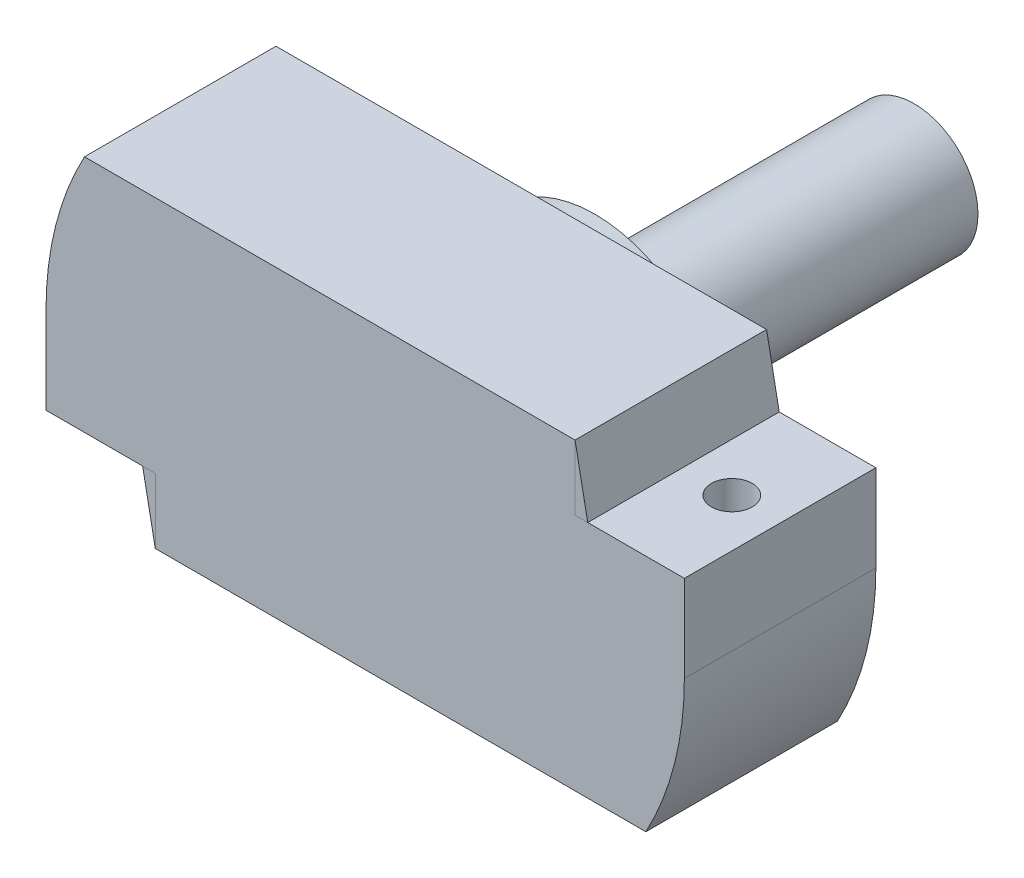
SolidWorks part; units mm, degrees
ref_plane "前视基准面" through (0, 0, 0) normal (0, 0, 1) x (1, 0, 0)
ref_plane "上视基准面" through (0, 0, 0) normal (0, 1, 0) x (1, 0, 0)
ref_plane "右视基准面" through (0, 0, 0) normal (1, 0, 0) x (0, 0, -1)
other "Configuration Table"
sketch "草图1" plane through (0, 0, 0) normal (0, 0, 1) x (1, 0, 0)
  circle A0 centre (0, 0) radius 5
  dimension "D1" = 10
extrude "凸台-拉伸1" add sketch "草图1" along normal blind 25
sketch "草图2" plane through (0, 0, 25) normal (0, 0, 1) x (1, 0, 0)
  circle A2 centre (0, 0) radius 10
  circle A3 centre (0, 0) radius 10
  dimension "D1" = 5
extrude "凸台-拉伸2" add sketch "草图2" along normal blind 3
sketch "草图3" plane through (0, 0, 28) normal (0, 0, 1) x (1, 0, 0)
  line L1 (-25, 11.9) -> (25, 11.9)
  line L2 (-25, 11.9) -> (-25, -11.9)
  line L3 (-25, -11.9) -> (25, -11.9)
  line L4 (25, 11.9) -> (25, -11.9)
  dimension "D1" = 23.8
  dimension "D2" = 50
  dimension "D3" = 25
  dimension "D4" = 11.9
extrude "凸台-拉伸3" add sketch "草图3" along normal blind 15
sketch "草图4" plane through (0, 0, 43) normal (0, 0, 1) x (1, 0, 0)
  line L4 (-25, 11.9) -> (-25, -11.9)
  line L5 (-25, -11.9) -> (25, -11.9)
  line L6 (25, -11.9) -> (25, 11.9)
  line L7 (25, 11.9) -> (-25, 11.9)
  line L8 (-25, 11.9) -> (-25, 0)
  line L9 (21.9861, -11.9) -> (25, -11.9)
  line L10 (25, -11.9) -> (25, 0)
  line L11 (-21.9861, 11.9) -> (-25, 11.9)
  arc A0 (21.9861, -11.9) -> (25, 0) centre (0, 0) ccw
  arc A1 (-21.9861, 11.9) -> (-25, 0) centre (0, 0) ccw
  dimension "D1" = 50
  dimension "D2" = 0
extrude "切除-拉伸1" cut sketch "草图4" against normal through all
sketch "草图5" plane through (0, 11.9, 0) normal (0, 1, 0) x (1, 0, 0)
  line L0 (25, -28) -> (-21.9861, -28) construction
  line L1 (16.44, -28) -> (25, -28)
  line L2 (16.44, -28) -> (16.44, -43)
  line L3 (16.44, -43) -> (25, -43)
  line L4 (25, -28) -> (25, -43)
  dimension "D1" = 8.56
extrude "切除-拉伸2" cut sketch "草图5" against normal blind 5.1
sketch "草图6" plane through (0, 6.8, 0) normal (0, 1, 0) x (1, 0, 0)
  line L0 (16.44, -28) -> (16.44, -43) construction
  circle A0 centre (21.22, -35.5) radius 1.6
  dimension "D1" = 3.2
  dimension "D2" = 4.78
extrude "切除-拉伸3" cut sketch "草图6" against normal blind 10
sketch "草图7" plane through (0, -11.9, 0) normal (0, -1, 0) x (1, 0, 0)
  line L0 (-25, 28) -> (21.9861, 28) construction
  line L1 (-25, 43) -> (-16.44, 43)
  line L2 (-25, 43) -> (-25, 28)
  line L3 (-25, 28) -> (-16.44, 28)
  line L4 (-16.44, 43) -> (-16.44, 28)
  dimension "D1" = 8.56
extrude "切除-拉伸4" cut sketch "草图7" against normal blind 5.1
sketch "草图8" plane through (0, -6.8, 0) normal (0, -1, 0) x (1, 0, 0)
  line L1 (-16.44, 28) -> (-16.44, 43) construction
  circle A0 centre (-21.22, 35.5) radius 1.6
  dimension "D1" = 3.2
  dimension "D2" = 4.78
extrude "切除-拉伸5" cut sketch "草图8" against normal blind 10
sketch "草图9" plane through (0, 0, 43) normal (0, 0, 1) x (1, 0, 0)
  line L0 (16.44, 11.9) -> (17.4313, 6.8)
  line L1 (16.44, 6.8) -> (25, 6.8) construction
  line L2 (-16.44, -11.9) -> (-17.4313, -6.8)
  line L3 (-16.44, -6.8) -> (-25, -6.8) construction
  line L4 (-17.4313, -6.8) -> (-16.44, -6.8)
  line L5 (-16.44, -6.8) -> (-16.44, -11.9)
  line L6 (16.44, 11.9) -> (16.44, 6.8)
  line L7 (16.44, 6.8) -> (17.4313, 6.8)
extrude "凸台-拉伸4" add sketch "草图9" against normal blind 15 separate body
